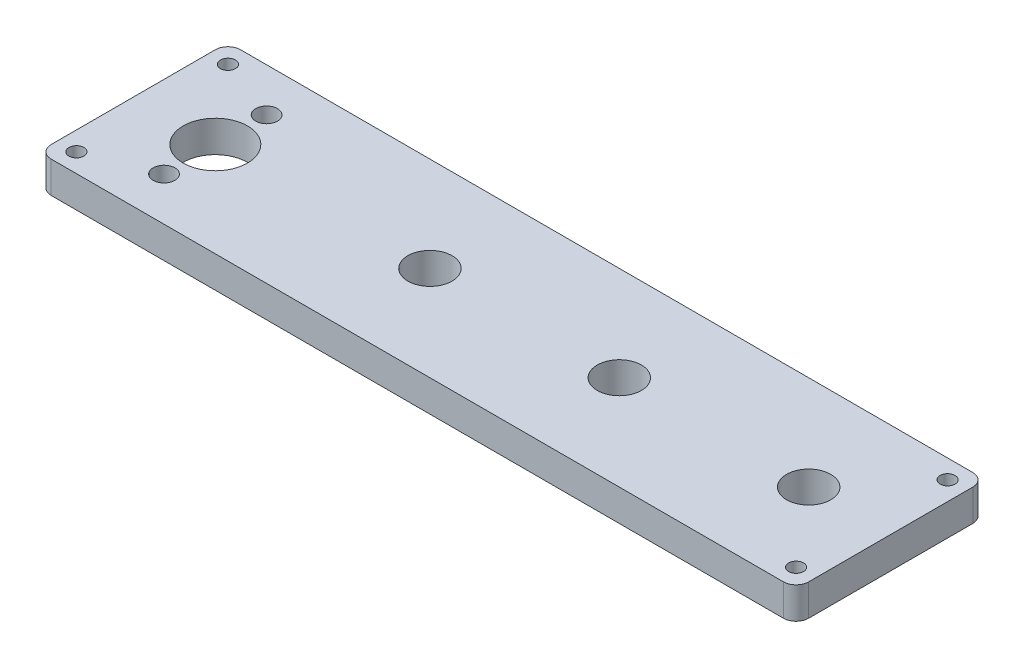
SolidWorks part; units mm, degrees
material "Acrylic (Medium-high impact)"
ref_plane "Front Plane" through (0, 0, 0) normal (0, 0, 1) x (1, 0, 0)
ref_plane "Top Plane" through (0, 0, 0) normal (0, 1, 0) x (1, 0, 0)
ref_plane "Right Plane" through (0, 0, 0) normal (1, 0, 0) x (0, 0, -1)
ref_plane "Plane1" through (0, 0, 0) normal (0, -1, 0) x (1, 0, 0)
sketch "Sketch1" plane through (0, 0, 0) normal (0, -1, 0) x (1, 0, 0)
  line L0 (-35.56, -19.05) -> (111.76, -19.05)
  line L1 (114.3, -16.51) -> (114.3, 16.51)
  line L2 (111.76, 19.05) -> (-35.56, 19.05)
  line L3 (-38.1, 16.51) -> (-38.1, -16.51)
  line L4 (0, 0) -> (0, 12.2265) construction
  line L5 (-21.59, -10.3188) -> (-21.59, 10.3188) construction
  circle A0 centre (59.69, 0) radius 4.445
  circle A1 centre (97.79, 0) radius 4.445
  circle A2 centre (-21.59, 0) radius 6.477
  circle A3 centre (-21.59, -10.3188) radius 2.1908
  circle A4 centre (-21.59, 10.3188) radius 2.1908
  circle A10 centre (21.59, 0) radius 4.445
  arc A13 (111.76, -19.05) -> (114.3, -16.51) centre (111.76, -16.51) ccw
  arc A14 (114.3, 16.51) -> (111.76, 19.05) centre (111.76, 16.51) ccw
  arc A15 (-35.56, 19.05) -> (-38.1, 16.51) centre (-35.56, 16.51) ccw
  arc A16 (-38.1, -16.51) -> (-35.56, -19.05) centre (-35.56, -16.51) ccw
  circle A17 centre (-21.59, 0) radius 10.16 construction
  point P12 (-21.59, -8.128)
  point P13 (-21.59, 8.128)
  point P14 (-21.59, 0)
  dimension "D1" = 20.32
  dimension "D5" = 2.54
  dimension "D8" = 8.89
  dimension "D9" = 38.1
  dimension "D11" = 12.954
  dimension "D12" = 4.3815
  dimension "D2" = 43.18
  dimension "D3" = 152.4
  dimension "D4" = 38.1
  dimension "D6" = 19.05
  dimension "D7" = 38.1
  dimension "D10" = 38.1
  dimension "D13" = 10.3187
extrude "Boss-Extrude1" add sketch "Sketch1" against normal blind 6.35
ref_plane "Plane2" through (0, 0, 0) normal (0, 0, 1) x (1, 0, 0)
hole_wizard "Ø1.0mm Dowel Hole1" positions "Sketch3" profile "Sketch4" hole size "Ø1.0" standard "ANSI Metric"
sketch "Sketch3" plane through (0, 9.525, 0) normal (0, 1, 0) x (1, 0, 0)
  line L4 (-35.56, 19.05) -> (111.76, 19.05) construction
  line L5 (-38.1, -16.51) -> (-38.1, 16.51) construction
  line L6 (-38.1, -16.51) -> (-38.1, 16.51) construction
  line L7 (111.76, -19.05) -> (-35.56, -19.05) construction
  line L8 (114.3, 16.51) -> (114.3, -16.51) construction
  line L9 (-35.56, 19.05) -> (111.76, 19.05) construction
  point P0 (-34.29, 15.24)
  point P2 (-34.29, -15.24)
  point P4 (110.49, -15.24)
  point P6 (110.49, 15.24)
  dimension "D1" = 3.81
  dimension "D2" = 3.81
  dimension "D3" = 3.81
  dimension "D4" = 3.81
  dimension "D5" = 3.81
  dimension "D6" = 3.81
  dimension "D7" = 3.81
  dimension "D8" = 3.81
sketch "Sketch4" plane through (-34.29, 9.525, -15.24) normal (1, 0, 0) x (0, 0, 1)
  line L0 (0, 0) -> (0, 10.9081)
  line L1 (0, 10.9081) -> (1.5113, 10)
  line L2 (1.5113, 10) -> (1.5113, 0)
  line L5 (1.5113, 0) -> (0, 0)
  line L10 (0, 10.9081) -> (-1.5113, 10) construction
  line L11 (0, -6.35) -> (0, 107.95) construction
  dimension "Hole Dia." = 3.0226
  dimension "Hole Depth" = 10
  dimension "Drill Angle" = 118
hole_wizard "Ø1.0mm Dowel Hole2" positions "Sketch6" profile "Sketch7" hole size "Ø1.0" standard "ANSI Metric" end condition through all
sketch "Sketch6" plane through (0, 6.35, 0) normal (0, 1, 0) x (1, 0, 0)
  line L1 (-35.56, 19.05) -> (111.76, 19.05) construction
  line L2 (114.3, 16.51) -> (114.3, -16.51) construction
  point P0 (-34.29, 15.24)
  point P3 (110.49, 15.24)
  point P6 (110.49, -15.24)
  point P8 (-34.29, -15.24)
  dimension "D1" = 3.81
  dimension "D2" = 3.81
sketch "Sketch7" plane through (-34.29, 6.35, -15.24) normal (1, 0, 0) x (0, 0, 1)
  line L0 (0, 0) -> (0, 6.35)
  line L1 (0, 6.35) -> (1.5113, 6.35)
  line L2 (1.5113, 6.35) -> (1.5113, 0)
  line L5 (1.5113, 0) -> (0, 0)
  line L11 (0, -6.35) -> (0, 107.95) construction
  dimension "Thru Hole Dia." = 3.0226
  dimension "Thru Hole Depth" = 6.35
